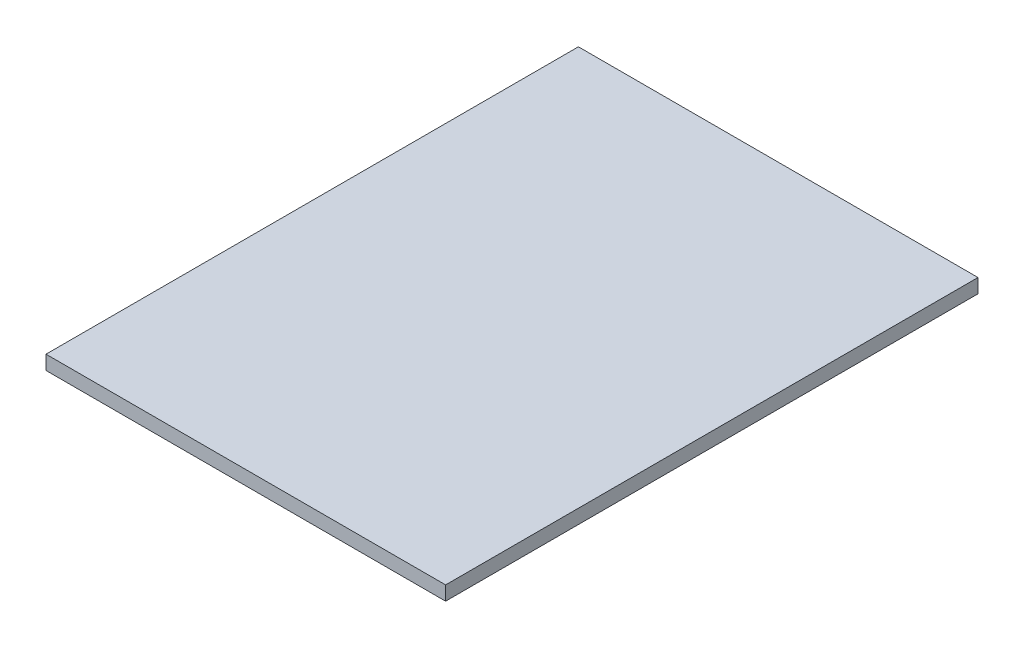
SolidWorks part; units mm, degrees
ref_plane "Front Plane" through (0, 0, 0) normal (0, 0, 1) x (1, 0, 0)
ref_plane "Top Plane" through (0, 0, 0) normal (0, 1, 0) x (1, 0, 0)
ref_plane "Right Plane" through (0, 0, 0) normal (1, 0, 0) x (0, 0, -1)
sketch "Sketch1" plane through (0, 0, 0) normal (0, 1, 0) x (1, 0, 0)
  line L1 (162.5, -216.5) -> (-162.5, -216.5)
  line L2 (162.5, -216.5) -> (162.5, 216.5)
  line L3 (162.5, 216.5) -> (-162.5, 216.5)
  line L4 (-162.5, -216.5) -> (-162.5, 216.5)
  line L5 (162.5, -216.5) -> (-162.5, 216.5) construction
  line L6 (162.5, 216.5) -> (-162.5, -216.5) construction
  point P0 (0, 0)
  dimension "D1" = 433
  dimension "D2" = 325
extrude "Boss-Extrude1" add sketch "Sketch1" along normal blind 11.5
